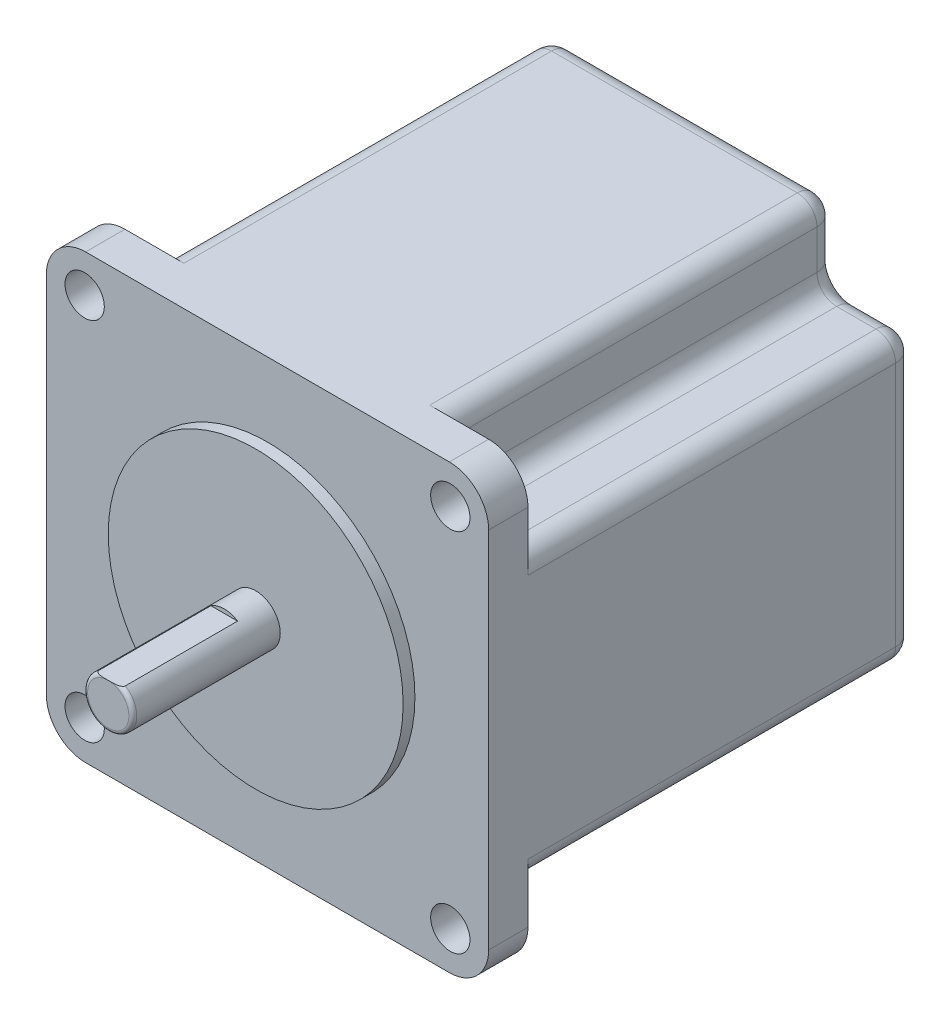
SolidWorks part; units mm, degrees
ref_plane "Front Plane" through (0, 0, 0) normal (0, 0, 1) x (1, 0, 0)
ref_plane "Top Plane" through (0, 0, 0) normal (0, 1, 0) x (1, 0, 0)
ref_plane "Right Plane" through (0, 0, 0) normal (1, 0, 0) x (0, 0, -1)
sketch "Sketch1" plane through (0, 0, 0) normal (0, 0, 1) x (1, 0, 0)
  line L1 (0, 0) -> (57.15, 0)
  line L2 (0, 0) -> (0, 57.15)
  line L3 (0, 57.15) -> (57.15, 57.15)
  line L4 (57.15, 0) -> (57.15, 57.15)
  dimension "D1" = 57.15
  dimension "D2" = 57.15
extrude "Boss-Extrude1" add sketch "Sketch1" along normal blind 55.118
sketch "Sketch2" plane through (0, 0, 55.118) normal (0, 0, 1) x (1, 0, 0)
  line L0 (28.575, 0) -> (28.575, 57.15) construction
  line L1 (0, 0) -> (57.15, 0) construction
  line L2 (57.15, 57.15) -> (0, 57.15) construction
  line L3 (57.15, 28.575) -> (0, 28.575) construction
  line L4 (57.15, 0) -> (57.15, 57.15) construction
  line L5 (0, 57.15) -> (0, 0) construction
  circle A0 centre (28.575, 28.575) radius 19.05
  dimension "D1" = 38.1
extrude "Boss-Extrude2" add sketch "Sketch2" along normal blind 1.524
sketch "Sketch3" plane through (0, 0, 56.642) normal (0, 0, 1) x (1, 0, 0)
  circle A0 centre (28.575, 28.575) radius 3.175
  dimension "D1" = 6.35
extrude "Boss-Extrude3" add sketch "Sketch3" along normal blind 19.05
sketch "Sketch18" plane through (0, 0, 0) normal (0, 0, -1) x (-1, 0, 0)
  line L1 (-10.16, 46.99) -> (10.16, 46.99)
  line L2 (-10.16, 46.99) -> (-10.16, 67.31)
  line L3 (-10.16, 67.31) -> (10.16, 67.31)
  line L4 (10.16, 46.99) -> (10.16, 67.31)
  line L5 (-10.16, 46.99) -> (10.16, 67.31) construction
  line L6 (-10.16, 67.31) -> (10.16, 46.99) construction
  point P0 (0, 57.15)
  dimension "D1" = 20.32
  dimension "D2" = 20.32
extrude "Cut-Extrude13" cut sketch "Sketch18" against normal blind 50.038
sketch "Sketch20" plane through (0, 0, 0) normal (0, 0, -1) x (-1, 0, 0)
  line L1 (10.16, 10.16) -> (-10.16, 10.16)
  line L2 (10.16, 10.16) -> (10.16, -10.16)
  line L3 (10.16, -10.16) -> (-10.16, -10.16)
  line L4 (-10.16, 10.16) -> (-10.16, -10.16)
  line L5 (10.16, 10.16) -> (-10.16, -10.16) construction
  line L6 (10.16, -10.16) -> (-10.16, 10.16) construction
  point P0 (0, 0)
  dimension "D1" = 20.32
  dimension "D2" = 20.32
extrude "Cut-Extrude14" cut sketch "Sketch20" against normal blind 50.038
sketch "Sketch21" plane through (0, 0, 0) normal (0, 0, -1) x (-1, 0, 0)
  line L1 (-46.99, 10.16) -> (-67.31, 10.16)
  line L2 (-46.99, 10.16) -> (-46.99, -10.16)
  line L3 (-46.99, -10.16) -> (-67.31, -10.16)
  line L4 (-67.31, 10.16) -> (-67.31, -10.16)
  line L5 (-46.99, 10.16) -> (-67.31, -10.16) construction
  line L6 (-46.99, -10.16) -> (-67.31, 10.16) construction
  point P1 (-57.15, 0)
  dimension "D1" = 20.32
  dimension "D2" = 20.32
extrude "Cut-Extrude15" cut sketch "Sketch21" against normal blind 50.038
sketch "Sketch22" plane through (0, 0, 0) normal (0, 0, -1) x (-1, 0, 0)
  line L1 (-67.31, 67.31) -> (-46.99, 67.31)
  line L2 (-67.31, 67.31) -> (-67.31, 46.99)
  line L3 (-67.31, 46.99) -> (-46.99, 46.99)
  line L4 (-46.99, 67.31) -> (-46.99, 46.99)
  line L5 (-67.31, 67.31) -> (-46.99, 46.99) construction
  line L6 (-67.31, 46.99) -> (-46.99, 67.31) construction
  point P0 (-57.15, 57.15)
  dimension "D1" = 20.32
  dimension "D2" = 20.32
extrude "Cut-Extrude16" cut sketch "Sketch22" against normal blind 50.038
sketch "Sketch11" plane through (0, 0, 55.118) normal (0, 0, 1) x (1, 0, 0)
  line L0 (4.953, 57.15) -> (4.953, 52.2331) construction
  line L1 (57.15, 57.15) -> (0, 57.15) construction
  line L2 (4.953, 52.2331) -> (0, 52.2331) construction
  line L3 (0, 57.15) -> (0, 0) construction
  circle A0 centre (4.953, 52.2331) radius 2.54
  dimension "D1" = 5.08
extrude "Cut-Extrude8" cut sketch "Sketch11" against normal through all
sketch "Sketch12" plane through (0, 0, 55.118) normal (0, 0, 1) x (1, 0, 0)
  line L0 (4.953, 52.2331) -> (52.197, 52.2331) construction
  circle A0 centre (52.197, 52.2331) radius 2.54
  dimension "D2" = 5.08
  dimension "D1" = 47.244
extrude "Cut-Extrude9" cut sketch "Sketch12" against normal through all
sketch "Sketch14" plane through (0, 0, 55.118) normal (0, 0, 1) x (1, 0, 0)
  line L0 (4.953, 52.2331) -> (4.953, 4.9891) construction
  line L1 (4.953, 4.9891) -> (52.197, 4.9891) construction
  circle A0 centre (4.953, 4.9891) radius 2.54
  dimension "D3" = 5.08
  dimension "D1" = 47.244
  dimension "D2" = 47.244
extrude "Cut-Extrude10" cut sketch "Sketch14" against normal through all
sketch "Sketch15" plane through (0, 0, 55.118) normal (0, 0, 1) x (1, 0, 0)
  line L0 (4.953, 4.9891) -> (52.197, 4.9891) construction
  line L1 (52.197, 52.2331) -> (52.197, 4.9891) construction
  circle A0 centre (52.197, 4.9891) radius 2.54
  dimension "D2" = 5.08
  dimension "D1" = 47.244
extrude "Cut-Extrude11" cut sketch "Sketch15" against normal through all
fillet "Fillet2" radius 5.08 4 edges at (57.15, 57.15, 52.578) (57.15, 0, 52.578) (0, 0, 52.578) (0, 57.15, 52.578)
fillet "Fillet4" radius 2.54 24 edges at (28.575, 57.15, 0) (0, 28.575, 0) (28.575, 0, 0) (57.15, 28.575, 0) (10.16, 52.07, 0) (5.08, 46.99, 0) (5.08, 10.16, 0) (10.16, 5.08, 0) (46.99, 5.08, 0) (52.07, 10.16, 0) (52.07, 46.99, 0) (46.99, 52.07, 0) (0, 46.99, 25.019) (10.16, 46.99, 25.019) (10.16, 57.15, 25.019) (46.99, 57.15, 25.019) (46.99, 46.99, 25.019) (57.15, 46.99, 25.019) (57.15, 10.16, 25.019) (46.99, 10.16, 25.019) (46.99, 0, 25.019) (10.16, 0, 25.019) (0, 10.16, 25.019) (10.16, 10.16, 25.019)
fillet "Fillet1" radius 0.508 1 edges at (31.75, 28.575, 75.692)
sketch "Sketch10" plane through (0, 0, 75.692) normal (0, 0, 1) x (1, 0, 0)
  line L0 (28.575, 25.4) -> (28.575, 31.242) construction
  line L2 (25.4566, 32.3482) -> (32.6055, 32.3482)
  line L3 (25.4566, 32.3482) -> (25.4566, 31.242)
  line L4 (25.4566, 31.242) -> (32.6055, 31.242)
  line L5 (32.6055, 32.3482) -> (32.6055, 31.242)
  circle A0 centre (28.575, 28.575) radius 3.175 construction
  circle A1 centre (28.575, 28.575) radius 3.175 construction
  dimension "D1" = 5.842
extrude "Cut-Extrude7" cut sketch "Sketch10" against normal blind 14.986
